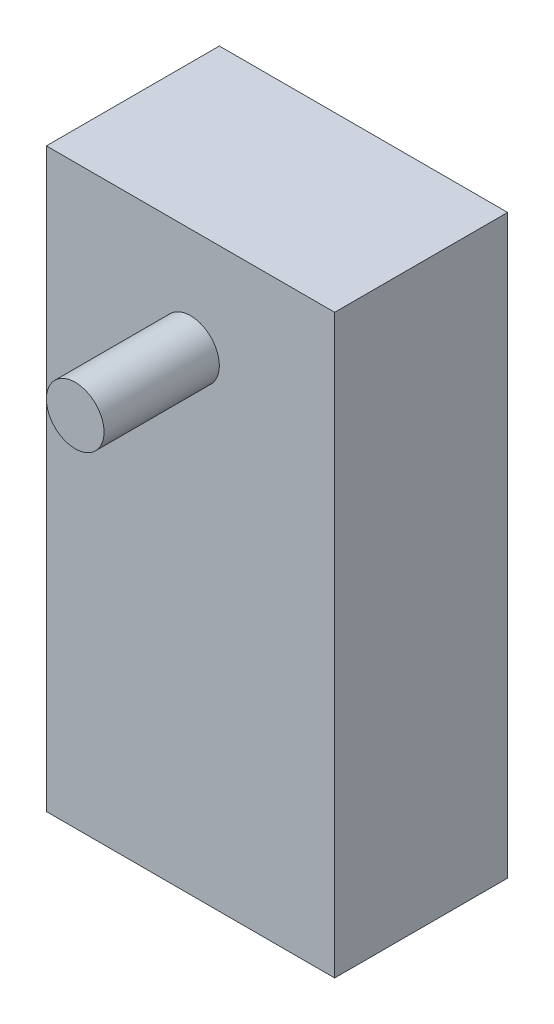
SolidWorks part; units mm, degrees
ref_plane "Front Plane" through (0, 0, 0) normal (0, 0, 1) x (1, 0, 0)
ref_plane "Top Plane" through (0, 0, 0) normal (0, 1, 0) x (1, 0, 0)
ref_plane "Right Plane" through (0, 0, 0) normal (1, 0, 0) x (0, 0, -1)
sketch "Sketch1" plane through (0, 0, 0) normal (0, 0, 1) x (1, 0, 0)
  line L1 (15.875, -31.75) -> (-15.875, -31.75)
  line L2 (15.875, -31.75) -> (15.875, 31.75)
  line L3 (15.875, 31.75) -> (-15.875, 31.75)
  line L4 (-15.875, -31.75) -> (-15.875, 31.75)
  line L5 (15.875, -31.75) -> (-15.875, 31.75) construction
  line L6 (15.875, 31.75) -> (-15.875, -31.75) construction
  point P0 (0, 0)
  dimension "D1" = 63.5
  dimension "D2" = 31.75
extrude "Boss-Extrude1" add sketch "Sketch1" along normal blind 19.05 separate body
sketch "Sketch2" plane through (0, 0, 19.05) normal (0, 0, 1) x (1, 0, 0)
  line L0 (-15.875, 31.75) -> (15.875, 31.75)
  line L1 (-15.875, 31.75) -> (-15.875, 14.2336)
  line L2 (15.875, 31.75) -> (15.875, 14.2336)
  line L3 (-15.875, 14.2336) -> (15.875, 14.2336)
  line L4 (0, 31.75) -> (0, 20.3156) construction
  circle A0 centre (0, 20.3156) radius 3.175
  point P8 (0, 31.75)
  point P9 (0, 0)
  point P11 (0, 0)
  dimension "D2" = 6.35
  dimension "D1" = 17.5164
  dimension "D3" = 11.4344
extrude "Boss-Extrude2" add sketch "Sketch2" along normal blind 12.7 contours A0
